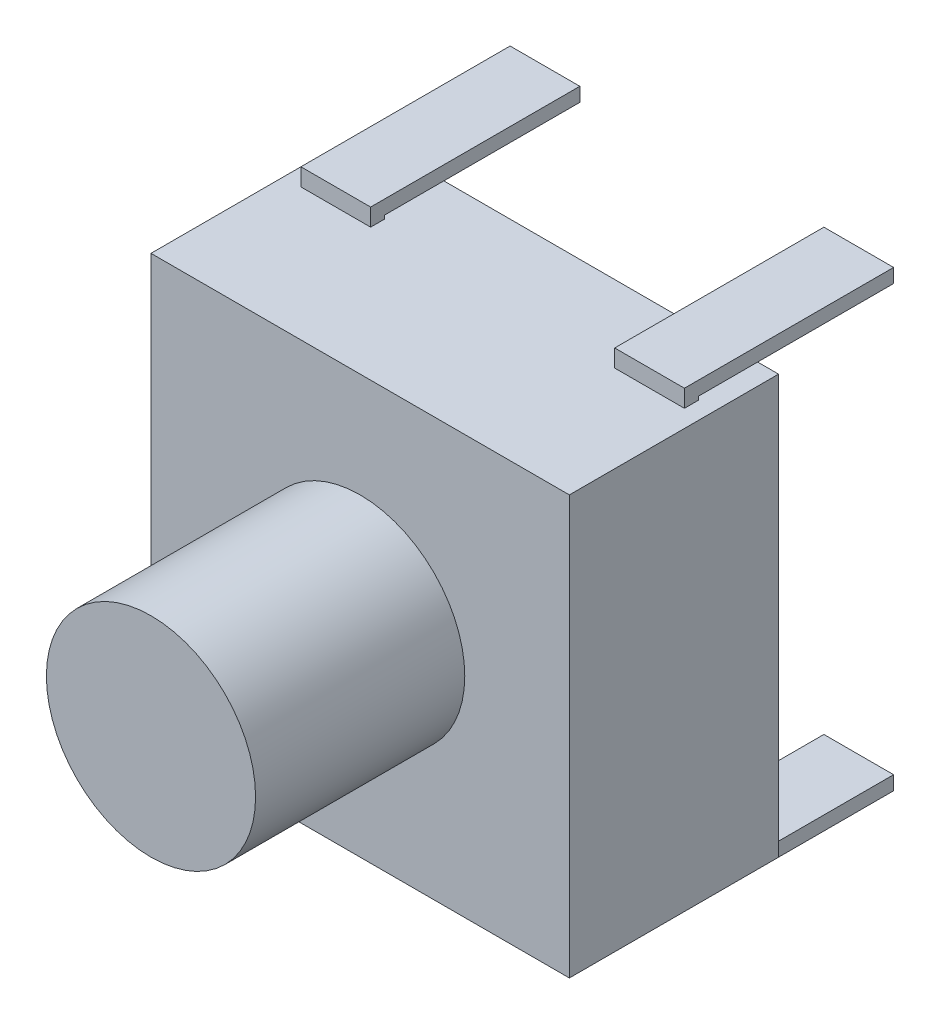
SolidWorks part; units mm, degrees
ref_plane "前视基准面" through (0, 0, 0) normal (0, 0, 1) x (1, 0, 0)
ref_plane "上视基准面" through (0, 0, 0) normal (0, 1, 0) x (1, 0, 0)
ref_plane "右视基准面" through (0, 0, 0) normal (1, 0, 0) x (0, 0, -1)
sketch "草图1" plane through (0, 0, 0) normal (0, 0, 1) x (1, 0, 0)
  line L0 (-1000, 0) -> (49000, 0) construction
  line L1 (0, -1000) -> (0, 49000) construction
  line L2 (-3, 3) -> (3, 3)
  line L3 (3, 3) -> (3, -3)
  line L4 (-3, 3) -> (-3, -3)
  line L5 (-3, -3) -> (3, -3)
  point P10 (0, 3)
  point P11 (3, 0)
  point P12 (-3, 0)
  dimension "D1" = 6
  dimension "D2" = 6
extrude "凸台-拉伸1" add sketch "草图1" along normal blind 3
sketch "草图2" plane through (0, 0, 3) normal (0, 0, 1) x (1, 0, 0)
  circle A0 centre (0, 0) radius 1.5
extrude "凸台-拉伸2" add sketch "草图2" along normal blind 3
sketch "草图4" plane through (0, -3, 0) normal (0, -1, 0) x (1, 0, 0)
  line L0 (0, -1000) -> (0, 49000) construction
  line L1 (2.25, 2.1495) -> (2.25, -0.7714) construction
  line L2 (-2.25, 2.1495) -> (-2.25, -0.7714) construction
  line L3 (-3.6318, 1) -> (3.4524, 1) construction
  line L4 (-3, 0) -> (3, 0) construction
  line L5 (1.75, 1.1) -> (2.75, 1.1)
  line L6 (2.75, 1.1) -> (2.75, 0.9)
  line L7 (1.75, 1.1) -> (1.75, 0.9)
  line L8 (1.75, 0.9) -> (2.75, 0.9)
  point P16 (2.25, 1.1)
  point P17 (2.75, 1)
  point P18 (1.75, 1)
  dimension "D1" = 4.5
  dimension "D2" = 1
  dimension "D3" = 0.2
  dimension "D4" = 1
ref_plane "基准面1" through (2.25, 0, 0) normal (1, 0, 0) x (0, 0, -1)
sketch "草图6" plane through (2.25, 0, 0) normal (1, 0, 0) x (0, 0, -1)
  line L0 (-1000, 0) -> (49000, 0) construction
  line L1 (-4.4082, -3.25) -> (1.7946, -3.25) construction
  line L2 (-4.4082, 3.25) -> (1.7946, 3.25) construction
  line L3 (-1.1, -3) -> (-1.1, -3.25)
  line L4 (-1.1, -3.25) -> (1.9, -3.25)
  dimension "D1" = 6.5
  dimension "D2" = 3
sweep "扫描3" add profiles "草图4" path "草图6"
mirror "镜向1" about plane through (0, 0, 0) normal (1, 0, 0) of "扫描3"
mirror "镜向2" about plane through (0, 0, 0) normal (0, 1, 0) of "镜向1", "扫描3"
